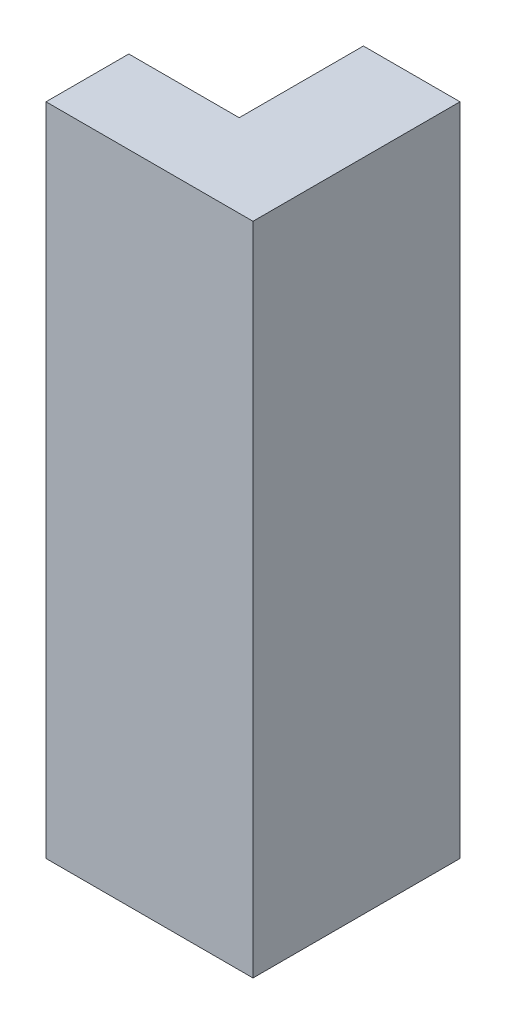
SolidWorks part; units mm, degrees
ref_plane "Front Plane" through (0, 0, 0) normal (0, 0, 1) x (1, 0, 0)
ref_plane "Top Plane" through (0, 0, 0) normal (0, 1, 0) x (1, 0, 0)
ref_plane "Right Plane" through (0, 0, 0) normal (1, 0, 0) x (0, 0, -1)
sketch "Sketch1" plane through (0, 0, 0) normal (0, 1, 0) x (1, 0, 0)
  line L0 (-287.5, -187.5) -> (87.5, -187.5)
  line L2 (-87.5, -37.5) -> (-87.5, 187.5)
  line L3 (-87.5, 187.5) -> (87.5, 187.5)
  line L4 (87.5, -187.5) -> (87.5, 187.5)
  line L5 (-87.5, 187.5) -> (87.5, -187.5) construction
  line L6 (-87.5, -187.5) -> (87.5, 187.5) construction
  line L9 (-87.5, -37.5) -> (-287.5, -37.5)
  line L10 (-287.5, -187.5) -> (-287.5, -37.5)
  point P0 (0, 0)
  point P10 (0, 0)
  dimension "D1" = 375
  dimension "D2" = 175
  dimension "D3" = 150
  dimension "D4" = 200
extrude "Boss-Extrude1" add sketch "Sketch1" along normal blind 1187.25
